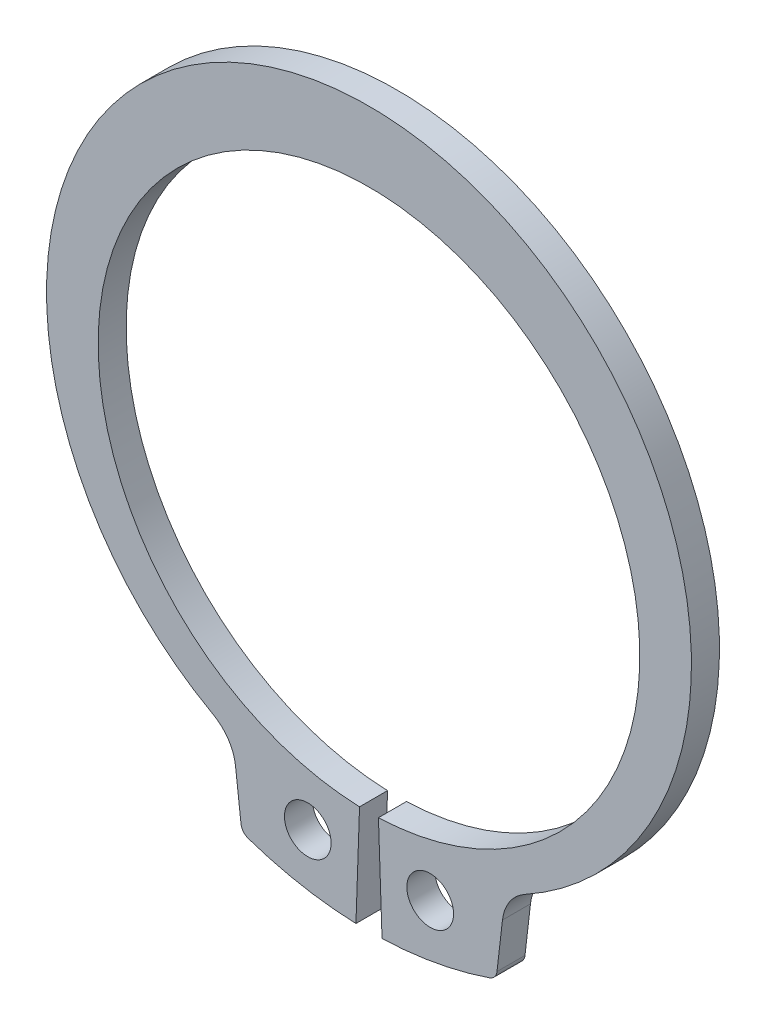
SolidWorks part; units mm, degrees
ref_plane "Front" through (0, 0, 0) normal (0, 0, 1) x (1, 0, 0)
ref_plane "Top" through (0, 0, 0) normal (0, 1, 0) x (1, 0, 0)
ref_plane "Right" through (0, 0, 0) normal (1, 0, 0) x (0, 0, -1)
sketch "Sketch1" plane through (0, 0, 0) normal (0, 0, 1) x (1, 0, 0)
  line L0 (0, 0) -> (-10.0459, -5.8) construction
  line L1 (0, 16) -> (0, -16) construction
  line L2 (-5.4478, -15.0543) -> (-5.8318, -11.7303) construction
  line L4 (-5.8318, -11.7303) -> (-6.4996, -13.0735) construction
  line L5 (-5.8318, -11.7303) -> (0, 0) construction
  line L6 (0, 11.6) -> (0, 14.6) construction
  line L7 (0, 14.6) -> (0, 13.1) construction
  line L8 (0, -11.6) -> (0, -16) construction
  line L9 (-3.0403, -15.7184) -> (0, 0) construction
  line L10 (0, 0) -> (-0.5587, -16) construction
  line L11 (-5.4478, -15.0543) -> (0, 0) construction
  line L12 (-5.7233, -12.6699) -> (-6.6751, -11.3018) construction
  line L13 (-6.1992, -11.9859) -> (-5.8318, -11.7303) construction
  line L14 (-2.2029, -11.3889) -> (-3.0403, -15.7184) construction
  line L15 (-2.6216, -13.5537) -> (-1.6398, -13.7436) construction
  arc A0 (0, 14.6) -> (-5.8318, -11.7303) centre (0, 0.789) ccw construction
  circle A2 centre (0, 0) radius 14.6 construction
  arc A3 (-5.4478, -15.0543) -> (-0.5587, -16) centre (0, 0) ccw construction
  circle A4 centre (0, 0) radius 11.6 construction
  circle A6 centre (-2.6216, -13.5537) radius 1 construction
  arc A7 (-6.6751, -11.3018) -> (-5.7233, -12.6699) centre (-7.5849, -12.9499) cw construction
  circle A9 centre (0, 0) radius 12.5 construction
  circle A10 centre (0, 0) radius 11.95 construction
  point P5 (-10.0459, -5.8)
  point P24 (-4.9681, -13.7287)
  point P35 (0, 14.6)
  point P36 (0, 11.6)
  point P37 (0, -11.6)
  point P38 (0, -16)
  dimension "Hole Diameter" = 2
  dimension "D10" = 1.8826
  dimension "For OD" = 25
  dimension "ID" = 23.2
  dimension "Max Sec." = 3
  dimension "Lug Height" = 4.4
  dimension "D6" = 2
  dimension "D5" = 3.3462
  dimension "D8" = 1.6667
  dimension "D3" = 120
  dimension "D2" = 5
  dimension "D4" = 1.6667
sketch "Sketch2" plane through (0, 0, 0) normal (-1, 0, 0) x (0, 1, 0)
  line L0 (-14.6, 0.6) -> (-14.6, -0.6) construction
  line L1 (14.6, -0.65) -> (14.6, 0.65) construction
  line L2 (0, 0.6) -> (0, -0.6) construction
  line L4 (-14.6, 0) -> (14.6, 0) construction
  point P3 (-14.6, 0)
  point P6 (0, 0)
  point P14 (14.6, 0)
  dimension "Thickness" = 1.2
  dimension "For Groove Width" = 1.3
sketch "Sketch4" plane through (0, 0, 0) normal (0, 0, 1) x (1, 0, 0)
  line L0 (-5.4478, -15.0543) -> (-5.8318, -11.7303) construction
  line L1 (-5.4478, -15.0543) -> (-5.8318, -11.7303)
  line L2 (0, 14.6) -> (0, 11.6)
  line L3 (-0.5587, -16) -> (-0.4048, -11.5929)
  line L4 (0, 0) -> (-0.5587, -16) construction
  arc A0 (0, 14.6) -> (-5.8318, -11.7303) centre (0, 0.789) ccw construction
  arc A1 (-5.4478, -15.0543) -> (-0.5587, -16) centre (0, 0) ccw construction
  circle A2 centre (-2.6216, -13.5537) radius 1 construction
  arc A4 (0, 14.6) -> (-5.8318, -11.7303) centre (0, 0.789) ccw
  arc A5 (-5.4478, -15.0543) -> (-0.5587, -16) centre (0, 0) ccw
  circle A6 centre (-2.6216, -13.5537) radius 1
  circle A7 centre (0, 0) radius 11.6 construction
  arc A8 (0, 11.6) -> (-0.4048, -11.5929) centre (0, 0) ccw
extrude "Boss-Extrude1" add sketch "Sketch4" along normal mid plane 1.2
fillet "Fillet1" radius 1.8826 1 edges at (-5.8318, -11.7303, 0)
fillet "Fillet2" radius 0.4707 1 edges at (-5.4478, -15.0543, 0)
mirror "Mirror1" about plane through (0, 14.6, 0.6) normal (-1, 0, 0) of bodies 109
sketch "Sketch3" plane through (0, 0, 0.6) normal (0, 0, 1) x (1, 0, 0)
  line L0 (5.9382, -9.9648) -> (6.6761, -11.3012) construction
  line L1 (6.6761, -11.3012) -> (8.0124, -10.5633) construction
  line L2 (0, 14.6) -> (0, 11.6) construction
  circle A0 centre (0, 0) radius 11.6 construction
  arc A1 (6.6761, -11.3012) -> (-6.6761, -11.3012) centre (0, 0.789) ccw construction
equation "\"D1@Fillet1\" = \"D10@Sketch1\""
equation "\"D1@Fillet2\" = \"D10@Sketch1\" / 4"
equation "\"Thickness@Boss-Extrude1\"  = \"Ring Thickness@Sketch5\""
equation "\"D2@Sketch1\"=\"Hole Diameter@Sketch1\"*2.5"
equation "\"D4@Sketch1\"=\"D2@Sketch1\"/3"
equation "\"D8@Sketch1\"=\"D4@Sketch1\""
